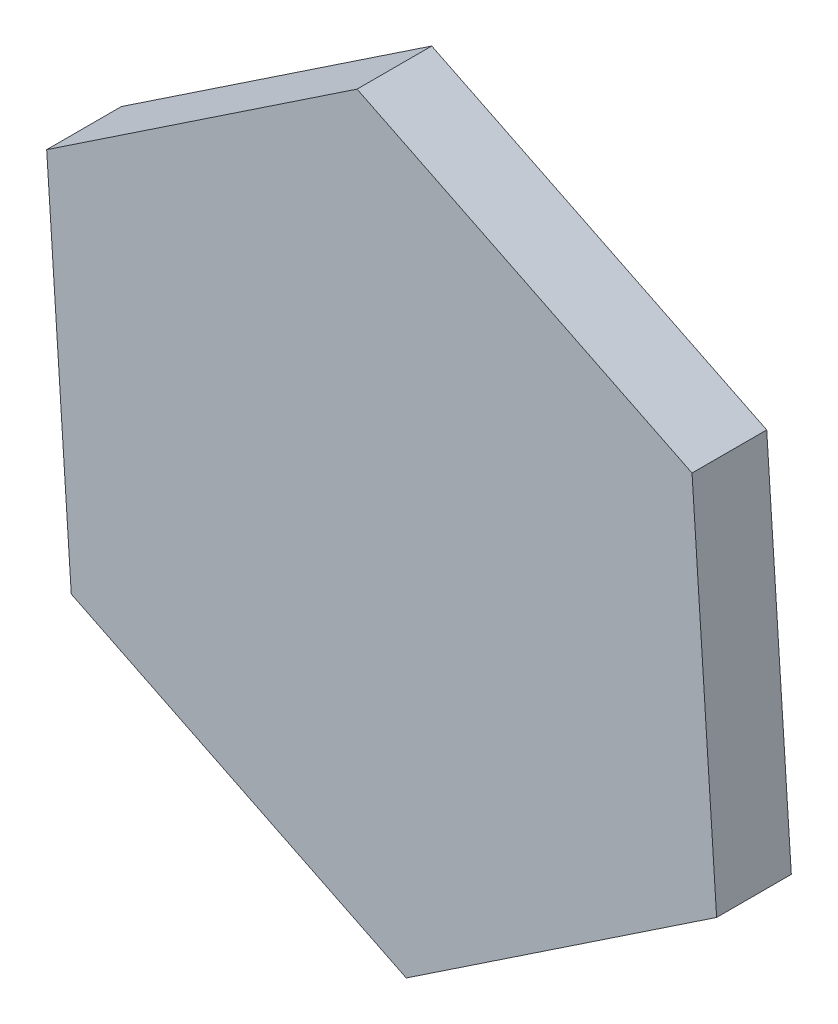
SolidWorks part; units mm, degrees
ref_plane "Plan de face" through (0, 0, 0) normal (0, 0, 1) x (1, 0, 0)
ref_plane "Plan de dessus" through (0, 0, 0) normal (0, 1, 0) x (1, 0, 0)
ref_plane "Plan de droite" through (0, 0, 0) normal (1, 0, 0) x (0, 0, -1)
sketch "Esquisse1" plane through (0, 0, 0) normal (0, 0, 1) x (1, 0, 0)
  line L1 (62.3394, 41.6989) -> (-4.9426, 74.837)
  line L2 (-4.9426, 74.837) -> (-67.282, 33.1381)
  line L3 (-67.282, 33.1381) -> (-62.3394, -41.6989)
  line L4 (-62.3394, -41.6989) -> (4.9426, -74.837)
  line L5 (4.9426, -74.837) -> (67.282, -33.1381)
  line L6 (67.282, -33.1381) -> (62.3394, 41.6989)
  circle A0 centre (0, 0) radius 64.9519 construction
  dimension "D1" = 150
extrude "Boss.-Extru.1" add sketch "Esquisse1" along normal blind 15
sketch "Esquisse2" plane through (0, 0, 15) normal (0, 0, 1) x (1, 0, 0)
  circle A0 centre (0, 0) radius 24.6153
